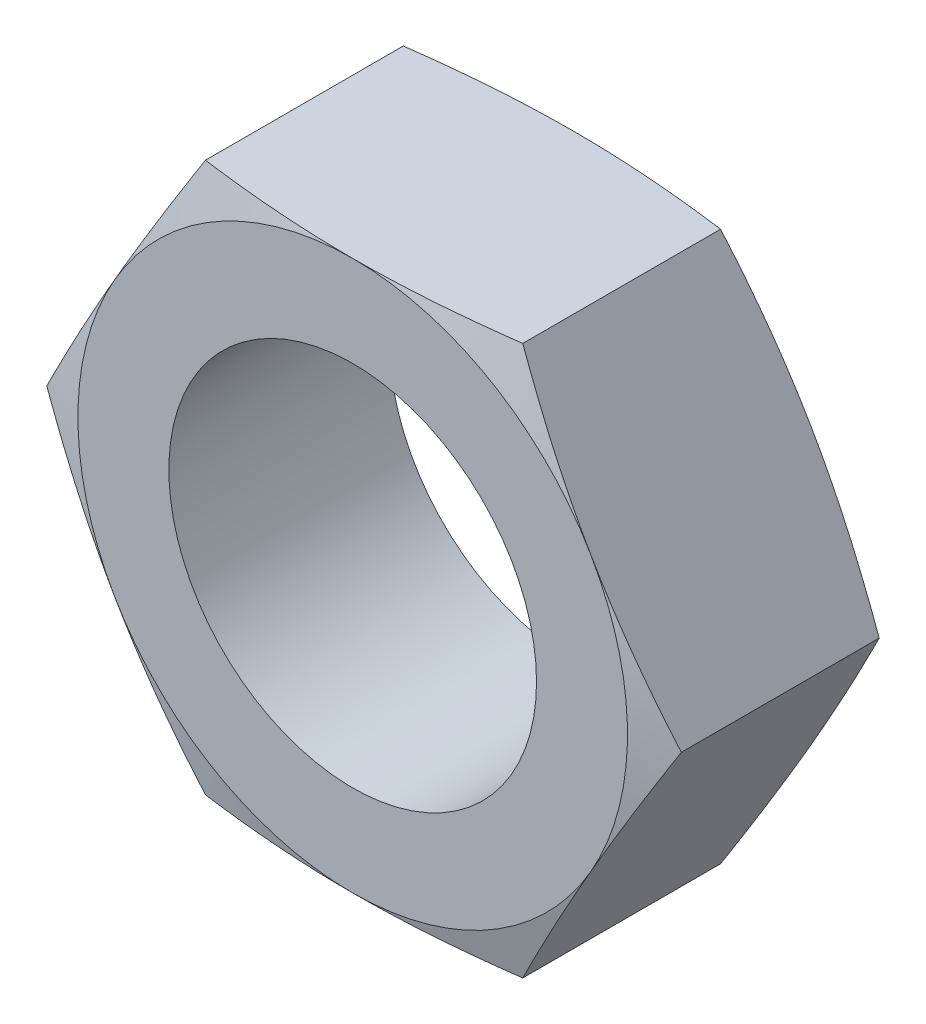
SolidWorks part; units mm, degrees
material "4级"
ref_plane "基准面1" through (0, 0, 0) normal (0, 0, 1) x (1, 0, 0)
ref_plane "基准面2" through (0, 0, 0) normal (0, 1, 0) x (1, 0, 0)
ref_plane "基准面3" through (0, 0, 0) normal (1, 0, 0) x (0, 0, -1)
sketch "尺寸草图" plane through (0, 0, 0) normal (0, 0, 1) x (1, 0, 0)
  line L0 (0, 0) -> (24.1005, 0)
  point P3 (5, 0)
  point P4 (1.5, 0)
  point P5 (8.63, 0)
  point P6 (5.6, 0)
  point P7 (6.4, 0)
  point P8 (8, 0)
  dimension "D" = 5
  dimension "e" = 8.63
  dimension "P1" = 1.5
  dimension "m" = 5.6
  dimension "mw" = 6.4
  dimension "s" = 8
sketch "草图1" plane through (0, 0, 0) normal (0, 0, 1) x (1, 0, 0)
  line L0 (-26.8088, 0) -> (37.1748, 0) construction
  line L1 (0, 25.0215) -> (0, -25.0215) construction
  line L3 (2.1575, 3.7369) -> (-2.1575, 3.7369)
  line L4 (-2.1575, 3.7369) -> (-4.315, 0)
  line L5 (-4.315, 0) -> (-2.1575, -3.7369)
  line L6 (-2.1575, -3.7369) -> (2.1575, -3.7369)
  line L7 (2.1575, -3.7369) -> (4.315, 0)
  line L8 (4.315, 0) -> (2.1575, 3.7369)
  circle A0 centre (0, 0) radius 3.7369 construction
  circle A1 centre (0, 0) radius 2.5
  dimension "D" = 5
  dimension "e" = 8.63
extrude "基体-拉伸" add sketch "草图1" along normal blind 3
cosmetic thread "装饰螺纹线1" parameters "D2"=5.25
cosmetic thread "装饰螺纹线2" parameters "D1"=3, "D2"=5.1
sketch "草图2" plane through (0, 0, 0) normal (0, 0, -1) x (-1, 0, 0)
  line L0 (-2.1575, 3.7369) -> (2.1575, 3.7369) construction
  circle A0 centre (0, 0) radius 3.7369
  circle A1 centre (0, 0) radius 2.5 construction
extrude "切除-拉伸1" cut sketch "草图2" against normal blind 38 draft 75 flip side to cut
sketch "草图3" plane through (0, 0, 3) normal (0, 0, 1) x (1, 0, 0)
  line L0 (4.315, 0) -> (2.1575, 3.7369) construction
  circle A0 centre (0, 0) radius 3.7369
extrude "切除-拉伸2" cut sketch "草图3" against normal blind 38 draft 75 flip side to cut
chamfer "倒角1" [suppressed] distance 0.2 angle 45
equation "\"e@草图1\" = \"e@尺寸草图\""
equation "\"D@草图1\" = \"D@尺寸草图\""
equation "\"D2@装饰螺纹线1\" = 1.05 * \"D@尺寸草图\""
